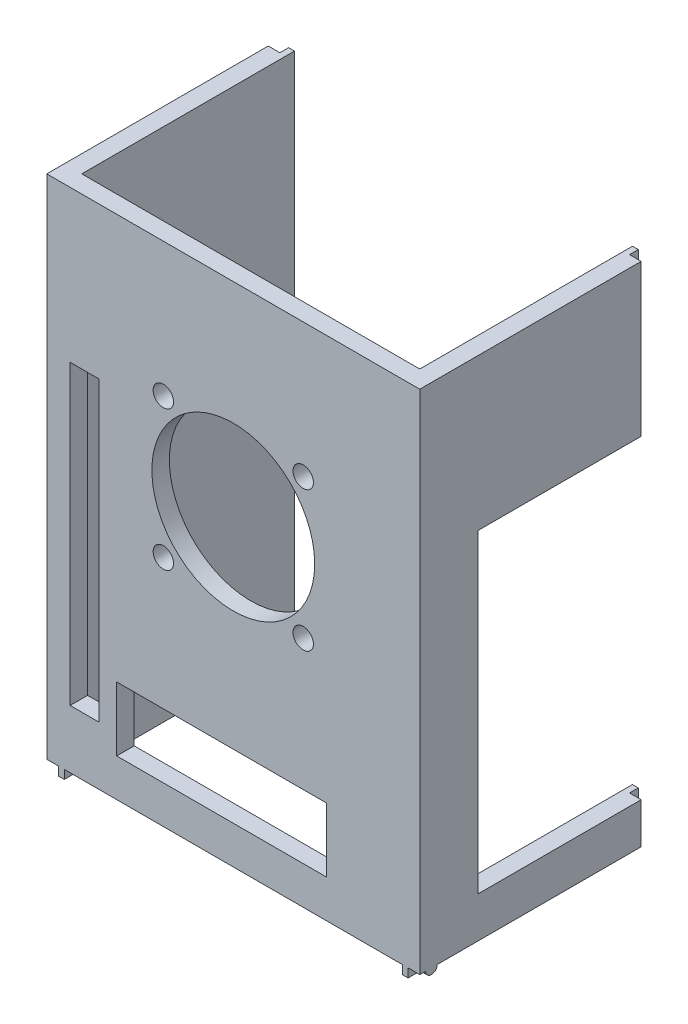
SolidWorks part; units mm, degrees
ref_plane "前视基准面" through (0, 0, 0) normal (0, 0, 1) x (1, 0, 0)
ref_plane "上视基准面" through (0, 0, 0) normal (0, 1, 0) x (1, 0, 0)
ref_plane "右视基准面" through (0, 0, 0) normal (1, 0, 0) x (0, 0, -1)
sketch "草图2" plane through (0, 0, 0) normal (0, 1, 0) x (1, 0, 0)
  line L0 (-3.2692, 5.7115) -> (-3.2692, 2.7115)
  line L1 (-3.2692, 2.7115) -> (-4.7692, 2.7115)
  line L2 (-4.7692, 2.7115) -> (-4.7692, -19.2885)
  line L3 (-4.7692, -19.2885) -> (57.2308, -19.2885)
  line L4 (57.2308, -19.2885) -> (57.2308, 2.7115)
  line L5 (57.2308, 2.7115) -> (55.7308, 2.7115)
  line L6 (55.7308, 2.7115) -> (55.7308, 5.7115)
  line L7 (55.7308, 5.7115) -> (54.2308, 5.7115)
  line L8 (54.2308, 5.7115) -> (54.2308, -16.2885)
  line L9 (54.2308, -16.2885) -> (-1.7692, -16.2885)
  line L10 (-1.7692, -16.2885) -> (-1.7692, 5.7115)
  line L11 (-1.7692, 5.7115) -> (-3.2692, 5.7115)
  dimension "D1" = 1.5
  dimension "D2" = 1.5
  dimension "D3" = 22
  dimension "D4" = 3
  dimension "D5" = 1.5
  dimension "D6" = 1.5
  dimension "D7" = 3
  dimension "D8" = 3
  dimension "D9" = 62
extrude "凸台-拉伸1" add sketch "草图2" along normal blind 88
sketch "草图3" plane through (0, 0, 0) normal (0, -1, 0) x (1, 0, 0)
  line L0 (26.2308, 19.2885) -> (26.2308, 3.3282) construction
  line L1 (-3.2692, -5.7115) -> (-1.7692, -5.7115)
  line L2 (-3.2692, -5.7115) -> (-3.2692, 16.2885)
  line L3 (-3.2692, 16.2885) -> (-1.7692, 16.2885)
  line L4 (-1.7692, -5.7115) -> (-1.7692, 16.2885)
  line L5 (-3.2692, -5.7115) -> (-1.7692, 16.2885) construction
  line L6 (-3.2692, 16.2885) -> (-1.7692, -5.7115) construction
  line L7 (-4.7692, 19.2885) -> (57.2308, 19.2885) construction
  line L8 (55.7308, 16.2885) -> (54.2308, -5.7115) construction
  line L9 (55.7308, -5.7115) -> (54.2308, 16.2885) construction
  line L10 (54.2308, -5.7115) -> (54.2308, 16.2885)
  line L11 (55.7308, 16.2885) -> (54.2308, 16.2885)
  line L12 (55.7308, -5.7115) -> (55.7308, 16.2885)
  line L13 (55.7308, -5.7115) -> (54.2308, -5.7115)
  point P4 (-2.5192, 5.2885)
  point P15 (54.9808, 5.2885)
extrude "凸台-拉伸2" add sketch "草图3" along normal blind 3
sketch "草图4" plane through (0, 0, -2.7115) normal (0, 0, -1) x (-1, 0, 0)
  line L0 (-55.7308, 88) -> (-55.7308, 0) construction
  line L1 (-55.7308, 16.69) -> (-54.2308, 16.69)
  line L2 (-55.7308, 16.69) -> (-55.7308, 44.69)
  line L3 (-55.7308, 44.69) -> (-54.2308, 44.69)
  line L4 (-54.2308, 16.69) -> (-54.2308, 44.69)
  line L5 (-55.7308, 16.69) -> (-54.2308, 44.69) construction
  line L6 (-55.7308, 44.69) -> (-54.2308, 16.69) construction
  line L7 (-57.2308, 0) -> (-55.7308, 0) construction
  point P4 (-54.9808, 30.69)
  dimension "D1" = 16.69
  dimension "D2" = 28
  dimension "D3" = 1.5
extrude "切除-拉伸1" cut sketch "草图4" along normal blind 13
sketch "草图5" plane through (0, 0, -2.7115) normal (0, 0, -1) x (-1, 0, 0)
  line L0 (-57.2308, 88) -> (-57.2308, 0) construction
  line L1 (-57.2308, 9) -> (-54.2308, 9)
  line L2 (-57.2308, 9) -> (-57.2308, 61)
  line L3 (-57.2308, 61) -> (-54.2308, 61)
  line L4 (-54.2308, 9) -> (-54.2308, 61)
  line L5 (-57.2308, 9) -> (-54.2308, 61) construction
  line L6 (-57.2308, 61) -> (-54.2308, 9) construction
  line L7 (-57.2308, 0) -> (-55.7308, 0) construction
  point P4 (-55.7308, 35)
  dimension "D1" = 3
  dimension "D2" = 9
  dimension "D3" = 52
extrude "切除-拉伸2" cut sketch "草图5" against normal mid plane 12
sketch "草图6" plane through (-4.7692, 0, 0) normal (-1, 0, 0) x (0, 0, 1)
  line L1 (-2.7115, 0) -> (19.2885, 0) construction
  circle A0 centre (17.2885, 0) radius 1
  dimension "D1" = 2
sketch "草图7" plane through (0, 0, 16.2885) normal (0, 0, 1) x (1, 0, 0)
  line L4 (55.7308, 0) -> (54.2308, 0)
  line L5 (54.2308, 0) -> (54.2308, -3)
  line L6 (54.2308, -3) -> (55.7308, -3)
  line L7 (55.7308, -3) -> (55.7308, 0)
  line L8 (55.7308, 0) -> (54.2308, 0)
  line L9 (54.2308, 0) -> (54.2308, -3)
  line L10 (54.2308, -3) -> (55.7308, -3)
  line L11 (55.7308, -3) -> (55.7308, 0)
  line L12 (-1.7692, 0) -> (-3.2692, 0)
  line L13 (-3.2692, 0) -> (-3.2692, -3)
  line L14 (-3.2692, -3) -> (-1.7692, -3)
  line L15 (-1.7692, -3) -> (-1.7692, 0)
  line L16 (-1.7692, 0) -> (-3.2692, 0)
  line L17 (-3.2692, 0) -> (-3.2692, -3)
  line L18 (-3.2692, -3) -> (-1.7692, -3)
  line L19 (-1.7692, -3) -> (-1.7692, 0)
  dimension "D1" = 0
  dimension "D2" = 0
extrude "凸台-拉伸4" add sketch "草图7" along normal up to surface (3 mm away) up to face at (26.2308, 44, 19.2885)
extrude "凸台-拉伸7" add sketch "草图6" against normal through all
sketch "草图8" plane through (57.2308, 0, 0) normal (1, 0, 0) x (0, 0, -1)
  line L9 (-19.2885, 0) -> (-18.2885, 0)
  line L10 (-16.2885, 0) -> (2.7115, 0)
  line L11 (2.7115, 0) -> (2.7115, 9)
  line L12 (2.7115, 9) -> (-3.2885, 9)
  line L13 (-3.2885, 9) -> (-3.2885, 61)
  line L14 (-3.2885, 61) -> (2.7115, 61)
  line L15 (2.7115, 61) -> (2.7115, 88)
  line L16 (2.7115, 88) -> (-19.2885, 88)
  line L17 (-19.2885, 88) -> (-19.2885, 0)
  line L18 (-19.2885, 0) -> (-18.2885, 0)
  line L19 (-16.2885, 0) -> (2.7115, 0)
  line L20 (2.7115, 0) -> (2.7115, 9)
  line L21 (2.7115, 9) -> (-3.2885, 9)
  line L22 (-3.2885, 9) -> (-3.2885, 61)
  line L23 (-3.2885, 61) -> (2.7115, 61)
  line L24 (2.7115, 61) -> (2.7115, 88)
  line L25 (2.7115, 88) -> (-19.2885, 88)
  line L26 (-19.2885, 88) -> (-19.2885, 0)
  arc A1 (-18.2885, 0) -> (-16.2885, 0) centre (-17.2885, 0) ccw
  arc A2 (-18.2885, 0) -> (-16.2885, 0) centre (-17.2885, 0) ccw
  dimension "D1" = 0
extrude "凸台-拉伸8" add sketch "草图8" along normal blind 1
sketch "草图9" plane through (-4.7692, 0, 0) normal (-1, 0, 0) x (0, 0, 1)
  line L5 (-2.7115, 0) -> (16.2885, 0)
  line L6 (18.2885, 0) -> (19.2885, 0)
  line L7 (19.2885, 0) -> (19.2885, 88)
  line L8 (19.2885, 88) -> (-2.7115, 88)
  line L9 (-2.7115, 88) -> (-2.7115, 0)
  line L10 (-2.7115, 0) -> (16.2885, 0)
  line L11 (18.2885, 0) -> (19.2885, 0)
  line L12 (19.2885, 0) -> (19.2885, 88)
  line L13 (19.2885, 88) -> (-2.7115, 88)
  line L14 (-2.7115, 88) -> (-2.7115, 0)
  arc A1 (16.2885, 0) -> (18.2885, 0) centre (17.2885, 0) ccw
  arc A2 (16.2885, 0) -> (18.2885, 0) centre (17.2885, 0) ccw
  dimension "D1" = 0
extrude "凸台-拉伸9" add sketch "草图9" along normal blind 1
sketch "草图10" plane through (-3.2692, 0, 0) normal (-1, 0, 0) x (0, 0, 1)
  line L7 (19.2885, 0) -> (18.2885, 0)
  line L8 (16.2885, 0) -> (-2.7115, 0)
  line L9 (-2.7115, 0) -> (-2.7115, 88)
  line L10 (-2.7115, 88) -> (-5.7115, 88)
  line L11 (-5.7115, 88) -> (-5.7115, -3)
  line L12 (-5.7115, -3) -> (19.2885, -3)
  line L13 (19.2885, -3) -> (19.2885, 0)
  line L14 (19.2885, 0) -> (18.2885, 0)
  line L15 (16.2885, 0) -> (-2.7115, 0)
  line L16 (-2.7115, 0) -> (-2.7115, 88)
  line L17 (-2.7115, 88) -> (-5.7115, 88)
  line L18 (-5.7115, 88) -> (-5.7115, -3)
  line L19 (-5.7115, -3) -> (19.2885, -3)
  line L20 (19.2885, -3) -> (19.2885, 0)
  arc A1 (16.2885, 0) -> (18.2885, 0) centre (17.2885, 0) ccw
  arc A2 (16.2885, 0) -> (18.2885, 0) centre (17.2885, 0) ccw
  dimension "D1" = 0
extrude "凸台-拉伸10" add sketch "草图10" along normal blind 1
sketch "草图11" plane through (55.7308, 0, 0) normal (1, 0, 0) x (0, 0, -1)
  line L7 (2.7115, 0) -> (-16.2885, 0)
  line L8 (-18.2885, 0) -> (-19.2885, 0)
  line L9 (-19.2885, 0) -> (-19.2885, -3)
  line L10 (-19.2885, -3) -> (5.7115, -3)
  line L11 (5.7115, -3) -> (5.7115, 9)
  line L12 (5.7115, 9) -> (2.7115, 9)
  line L13 (2.7115, 9) -> (2.7115, 0)
  line L14 (2.7115, 0) -> (-16.2885, 0)
  line L15 (-18.2885, 0) -> (-19.2885, 0)
  line L16 (-19.2885, 0) -> (-19.2885, -3)
  line L17 (-19.2885, -3) -> (5.7115, -3)
  line L18 (5.7115, -3) -> (5.7115, 9)
  line L19 (5.7115, 9) -> (2.7115, 9)
  line L20 (2.7115, 9) -> (2.7115, 0)
  arc A1 (-18.2885, 0) -> (-16.2885, 0) centre (-17.2885, 0) ccw
  arc A2 (-18.2885, 0) -> (-16.2885, 0) centre (-17.2885, 0) ccw
  dimension "D1" = 0
extrude "凸台-拉伸11" add sketch "草图11" along normal blind 1
sketch "草图12" plane through (55.7308, 0, 0) normal (1, 0, 0) x (0, 0, -1)
  line L4 (2.7115, 88) -> (2.7115, 61)
  line L5 (2.7115, 61) -> (5.7115, 61)
  line L6 (5.7115, 61) -> (5.7115, 88)
  line L7 (5.7115, 88) -> (2.7115, 88)
  line L8 (2.7115, 88) -> (2.7115, 61)
  line L9 (2.7115, 61) -> (5.7115, 61)
  line L10 (5.7115, 61) -> (5.7115, 88)
  line L11 (5.7115, 88) -> (2.7115, 88)
  dimension "D1" = 0
extrude "凸台-拉伸12" add sketch "草图12" along normal blind 1
sketch "草图13" plane through (-1.7692, 0, 0) normal (1, 0, 0) x (0, 0, -1)
  line L6 (-16.2885, 88) -> (-16.2885, 0)
  line L7 (-18.2885, 0) -> (-19.2885, 0)
  line L8 (-19.2885, 0) -> (-19.2885, -3)
  line L9 (-19.2885, -3) -> (5.7115, -3)
  line L10 (5.7115, -3) -> (5.7115, 88)
  line L11 (5.7115, 88) -> (-16.2885, 88)
  line L12 (-16.2885, 88) -> (-16.2885, 0)
  line L13 (-18.2885, 0) -> (-19.2885, 0)
  line L14 (-19.2885, 0) -> (-19.2885, -3)
  line L15 (-19.2885, -3) -> (5.7115, -3)
  line L16 (5.7115, -3) -> (5.7115, 88)
  line L17 (5.7115, 88) -> (-16.2885, 88)
  arc A1 (-18.2885, 0) -> (-16.2885, 0) centre (-17.2885, 0) ccw
  arc A2 (-18.2885, 0) -> (-16.2885, 0) centre (-17.2885, 0) ccw
  dimension "D1" = 0
extrude "切除-拉伸3" cut sketch "草图13" against normal blind 1
sketch "草图14" plane through (54.2308, 0, 0) normal (-1, 0, 0) x (0, 0, 1)
  line L10 (19.2885, 0) -> (18.2885, 0)
  line L11 (16.2885, 0) -> (16.2885, 88)
  line L12 (16.2885, 88) -> (-5.7115, 88)
  line L13 (-5.7115, 88) -> (-5.7115, 61)
  line L14 (-5.7115, 61) -> (3.2885, 61)
  line L15 (3.2885, 61) -> (3.2885, 9)
  line L16 (3.2885, 9) -> (-5.7115, 9)
  line L17 (-5.7115, 9) -> (-5.7115, -3)
  line L18 (-5.7115, -3) -> (19.2885, -3)
  line L19 (19.2885, -3) -> (19.2885, 0)
  line L20 (19.2885, 0) -> (18.2885, 0)
  line L21 (16.2885, 0) -> (16.2885, 88)
  line L22 (16.2885, 88) -> (-5.7115, 88)
  line L23 (-5.7115, 88) -> (-5.7115, 61)
  line L24 (-5.7115, 61) -> (3.2885, 61)
  line L25 (3.2885, 61) -> (3.2885, 9)
  line L26 (3.2885, 9) -> (-5.7115, 9)
  line L27 (-5.7115, 9) -> (-5.7115, -3)
  line L28 (-5.7115, -3) -> (19.2885, -3)
  line L29 (19.2885, -3) -> (19.2885, 0)
  arc A1 (16.2885, 0) -> (18.2885, 0) centre (17.2885, 0) ccw
  arc A2 (16.2885, 0) -> (18.2885, 0) centre (17.2885, 0) ccw
  dimension "D1" = 0
extrude "切除-拉伸4" cut sketch "草图14" against normal blind 1
sketch "草图15" plane through (0, -3, 0) normal (0, -1, 0) x (1, 0, 0)
  line L4 (-2.7692, -5.7115) -> (-2.7692, 19.2885)
  line L5 (-2.7692, 19.2885) -> (-4.2692, 19.2885)
  line L6 (-4.2692, 19.2885) -> (-4.2692, -5.7115)
  line L7 (-4.2692, -5.7115) -> (-2.7692, -5.7115)
  line L8 (-2.7692, -5.7115) -> (-2.7692, 19.2885)
  line L9 (-2.7692, 19.2885) -> (-4.2692, 19.2885)
  line L10 (-4.2692, 19.2885) -> (-4.2692, -5.7115)
  line L11 (-4.2692, -5.7115) -> (-2.7692, -5.7115)
  dimension "D1" = 0
extrude "切除-拉伸5" cut sketch "草图15" against normal blind 1
sketch "草图16" plane through (0, -3, 0) normal (0, -1, 0) x (1, 0, 0)
  line L4 (56.7308, 19.2885) -> (55.2308, 19.2885)
  line L5 (55.2308, 19.2885) -> (55.2308, -5.7115)
  line L6 (55.2308, -5.7115) -> (56.7308, -5.7115)
  line L7 (56.7308, -5.7115) -> (56.7308, 19.2885)
  line L8 (56.7308, 19.2885) -> (55.2308, 19.2885)
  line L9 (55.2308, 19.2885) -> (55.2308, -5.7115)
  line L10 (55.2308, -5.7115) -> (56.7308, -5.7115)
  line L11 (56.7308, -5.7115) -> (56.7308, 19.2885)
  dimension "D1" = 0
extrude "切除-拉伸6" cut sketch "草图16" against normal blind 1
sketch "草图17" plane through (0, 0, -5.7115) normal (0, 0, -1) x (-1, 0, 0)
  line L4 (2.7692, -2) -> (4.2692, -2)
  line L5 (4.2692, -2) -> (4.2692, 88)
  line L6 (4.2692, 88) -> (2.7692, 88)
  line L7 (2.7692, 88) -> (2.7692, -2)
  line L8 (2.7692, -2) -> (4.2692, -2)
  line L9 (4.2692, -2) -> (4.2692, 88)
  line L10 (4.2692, 88) -> (2.7692, 88)
  line L11 (2.7692, 88) -> (2.7692, -2)
  dimension "D1" = 0
extrude "切除-拉伸7" cut sketch "草图17" against normal blind 1
sketch "草图18" plane through (0, 0, -5.7115) normal (0, 0, -1) x (-1, 0, 0)
  line L4 (-56.7308, -2) -> (-55.2308, -2)
  line L5 (-55.2308, -2) -> (-55.2308, 9)
  line L6 (-55.2308, 9) -> (-56.7308, 9)
  line L7 (-56.7308, 9) -> (-56.7308, -2)
  line L8 (-56.7308, -2) -> (-55.2308, -2)
  line L9 (-55.2308, -2) -> (-55.2308, 9)
  line L10 (-55.2308, 9) -> (-56.7308, 9)
  line L11 (-56.7308, 9) -> (-56.7308, -2)
  dimension "D1" = 0
extrude "切除-拉伸8" cut sketch "草图18" against normal blind 1
sketch "草图19" plane through (0, 0, -5.7115) normal (0, 0, -1) x (-1, 0, 0)
  line L4 (-55.2308, 61) -> (-55.2308, 88)
  line L5 (-55.2308, 88) -> (-56.7308, 88)
  line L6 (-56.7308, 88) -> (-56.7308, 61)
  line L7 (-56.7308, 61) -> (-55.2308, 61)
  line L8 (-55.2308, 61) -> (-55.2308, 88)
  line L9 (-55.2308, 88) -> (-56.7308, 88)
  line L10 (-56.7308, 88) -> (-56.7308, 61)
  line L11 (-56.7308, 61) -> (-55.2308, 61)
  dimension "D1" = 0
extrude "切除-拉伸9" cut sketch "草图19" against normal blind 1
sketch "草图20" plane through (0, 0, 19.2885) normal (0, 0, 1) x (1, 0, 0)
  line L12 (55.2308, -2) -> (56.7308, -2)
  line L13 (56.7308, -2) -> (56.7308, 0)
  line L14 (56.7308, 0) -> (58.2308, 0)
  line L15 (58.2308, 0) -> (58.2308, 88)
  line L16 (58.2308, 88) -> (-5.7692, 88)
  line L17 (-5.7692, 88) -> (-5.7692, 0)
  line L18 (-5.7692, 0) -> (-4.2692, 0)
  line L19 (-4.2692, 0) -> (-4.2692, -2)
  line L20 (-4.2692, -2) -> (-2.7692, -2)
  line L21 (-2.7692, -2) -> (-2.7692, 0)
  line L22 (-2.7692, 0) -> (55.2308, 0)
  line L23 (55.2308, 0) -> (55.2308, -2)
  line L24 (55.2308, -2) -> (56.7308, -2)
  line L25 (56.7308, -2) -> (56.7308, 0)
  line L26 (56.7308, 0) -> (58.2308, 0)
  line L27 (58.2308, 0) -> (58.2308, 88)
  line L28 (58.2308, 88) -> (-5.7692, 88)
  line L29 (-5.7692, 88) -> (-5.7692, 0)
  line L30 (-5.7692, 0) -> (-4.2692, 0)
  line L31 (-4.2692, 0) -> (-4.2692, -2)
  line L32 (-4.2692, -2) -> (-2.7692, -2)
  line L33 (-2.7692, -2) -> (-2.7692, 0)
  line L34 (-2.7692, 0) -> (55.2308, 0)
  line L35 (55.2308, 0) -> (55.2308, -2)
  dimension "D1" = 0
extrude "凸台-拉伸13" add sketch "草图20" along normal blind 1
sketch "草图21" plane through (0, 0, 16.2885) normal (0, 0, -1) x (-1, 0, 0)
  line L4 (-55.2308, 0) -> (2.7692, 0)
  line L5 (2.7692, 0) -> (2.7692, 88)
  line L6 (2.7692, 88) -> (-55.2308, 88)
  line L7 (-55.2308, 88) -> (-55.2308, 0)
  line L8 (-55.2308, 0) -> (2.7692, 0)
  line L9 (2.7692, 0) -> (2.7692, 88)
  line L10 (2.7692, 88) -> (-55.2308, 88)
  line L11 (-55.2308, 88) -> (-55.2308, 0)
  dimension "D1" = 0
extrude "切除-拉伸10" cut sketch "草图21" against normal blind 1
sketch "草图22" plane through (0, 88, 0) normal (0, 1, 0) x (1, 0, 0)
  line L12 (55.2308, 4.7115) -> (55.2308, -17.2885)
  line L13 (55.2308, -17.2885) -> (-2.7692, -17.2885)
  line L14 (-2.7692, -17.2885) -> (-2.7692, 4.7115)
  line L15 (-2.7692, 4.7115) -> (-4.2692, 4.7115)
  line L16 (-4.2692, 4.7115) -> (-4.2692, 2.7115)
  line L17 (-4.2692, 2.7115) -> (-5.7692, 2.7115)
  line L18 (-5.7692, 2.7115) -> (-5.7692, -20.2885)
  line L19 (-5.7692, -20.2885) -> (58.2308, -20.2885)
  line L20 (58.2308, -20.2885) -> (58.2308, 2.7115)
  line L21 (58.2308, 2.7115) -> (56.7308, 2.7115)
  line L22 (56.7308, 2.7115) -> (56.7308, 4.7115)
  line L23 (56.7308, 4.7115) -> (55.2308, 4.7115)
  line L24 (55.2308, 4.7115) -> (55.2308, -17.2885)
  line L25 (55.2308, -17.2885) -> (-2.7692, -17.2885)
  line L26 (-2.7692, -17.2885) -> (-2.7692, 4.7115)
  line L27 (-2.7692, 4.7115) -> (-4.2692, 4.7115)
  line L28 (-4.2692, 4.7115) -> (-4.2692, 2.7115)
  line L29 (-4.2692, 2.7115) -> (-5.7692, 2.7115)
  line L30 (-5.7692, 2.7115) -> (-5.7692, -20.2885)
  line L31 (-5.7692, -20.2885) -> (58.2308, -20.2885)
  line L32 (58.2308, -20.2885) -> (58.2308, 2.7115)
  line L33 (58.2308, 2.7115) -> (56.7308, 2.7115)
  line L34 (56.7308, 2.7115) -> (56.7308, 4.7115)
  line L35 (56.7308, 4.7115) -> (55.2308, 4.7115)
  dimension "D1" = 0
extrude "切除-拉伸11" cut sketch "草图22" against normal blind 1
sketch "草图23" plane through (0, -2, 0) normal (0, -1, 0) x (1, 0, 0)
  line L4 (-4.2692, 20.2885) -> (-4.2692, -4.7115)
  line L5 (-4.2692, -4.7115) -> (-2.7692, -4.7115)
  line L6 (-2.7692, -4.7115) -> (-2.7692, 20.2885)
  line L7 (-2.7692, 20.2885) -> (-4.2692, 20.2885)
  line L8 (-4.2692, 20.2885) -> (-4.2692, -4.7115)
  line L9 (-4.2692, -4.7115) -> (-2.7692, -4.7115)
  line L10 (-2.7692, -4.7115) -> (-2.7692, 20.2885)
  line L11 (-2.7692, 20.2885) -> (-4.2692, 20.2885)
  dimension "D1" = 0
extrude "切除-拉伸12" cut sketch "草图23" against normal blind 0.5
sketch "草图24" plane through (0, -2, 0) normal (0, -1, 0) x (1, 0, 0)
  line L4 (55.2308, 20.2885) -> (55.2308, -4.7115)
  line L5 (55.2308, -4.7115) -> (56.7308, -4.7115)
  line L6 (56.7308, -4.7115) -> (56.7308, 20.2885)
  line L7 (56.7308, 20.2885) -> (55.2308, 20.2885)
  line L8 (55.2308, 20.2885) -> (55.2308, -4.7115)
  line L9 (55.2308, -4.7115) -> (56.7308, -4.7115)
  line L10 (56.7308, -4.7115) -> (56.7308, 20.2885)
  line L11 (56.7308, 20.2885) -> (55.2308, 20.2885)
  dimension "D1" = 0
extrude "切除-拉伸13" cut sketch "草图24" against normal blind 0.5
sketch "草图25" plane through (0, 0, -4.7115) normal (0, 0, -1) x (-1, 0, 0)
  line L4 (2.7692, 87) -> (2.7692, -1.5)
  line L5 (2.7692, -1.5) -> (4.2692, -1.5)
  line L6 (4.2692, -1.5) -> (4.2692, 87)
  line L7 (4.2692, 87) -> (2.7692, 87)
  line L8 (2.7692, 87) -> (2.7692, -1.5)
  line L9 (2.7692, -1.5) -> (4.2692, -1.5)
  line L10 (4.2692, -1.5) -> (4.2692, 87)
  line L11 (4.2692, 87) -> (2.7692, 87)
  dimension "D1" = 0
extrude "切除-拉伸14" cut sketch "草图25" against normal blind 0.5
sketch "草图26" plane through (0, 0, -4.7115) normal (0, 0, -1) x (-1, 0, 0)
  line L4 (-55.2308, 61) -> (-55.2308, 87)
  line L5 (-55.2308, 87) -> (-56.7308, 87)
  line L6 (-56.7308, 87) -> (-56.7308, 61)
  line L7 (-56.7308, 61) -> (-55.2308, 61)
  line L8 (-55.2308, 61) -> (-55.2308, 87)
  line L9 (-55.2308, 87) -> (-56.7308, 87)
  line L10 (-56.7308, 87) -> (-56.7308, 61)
  line L11 (-56.7308, 61) -> (-55.2308, 61)
  dimension "D1" = 0
extrude "切除-拉伸15" cut sketch "草图26" against normal blind 0.5
sketch "草图27" plane through (0, 0, -4.7115) normal (0, 0, -1) x (-1, 0, 0)
  line L4 (-56.7308, 9) -> (-56.7308, -1.5)
  line L5 (-56.7308, -1.5) -> (-55.2308, -1.5)
  line L6 (-55.2308, -1.5) -> (-55.2308, 9)
  line L7 (-55.2308, 9) -> (-56.7308, 9)
  line L8 (-56.7308, 9) -> (-56.7308, -1.5)
  line L9 (-56.7308, -1.5) -> (-55.2308, -1.5)
  line L10 (-55.2308, -1.5) -> (-55.2308, 9)
  line L11 (-55.2308, 9) -> (-56.7308, 9)
  dimension "D1" = 0
extrude "切除-拉伸16" cut sketch "草图27" against normal blind 0.5
sketch "草图28" plane through (-4.2692, 0, 0) normal (-1, 0, 0) x (0, 0, 1)
  line L7 (-2.7115, 87) -> (-4.2115, 87)
  line L8 (-4.2115, 87) -> (-4.2115, -1.5)
  line L9 (-4.2115, -1.5) -> (20.2885, -1.5)
  line L10 (20.2885, -1.5) -> (20.2885, 0)
  line L11 (20.2885, 0) -> (18.2885, 0)
  line L12 (16.2885, 0) -> (-2.7115, 0)
  line L13 (-2.7115, 0) -> (-2.7115, 87)
  line L14 (-2.7115, 87) -> (-4.2115, 87)
  line L15 (-4.2115, 87) -> (-4.2115, -1.5)
  line L16 (-4.2115, -1.5) -> (20.2885, -1.5)
  line L17 (20.2885, -1.5) -> (20.2885, 0)
  line L18 (20.2885, 0) -> (18.2885, 0)
  line L19 (16.2885, 0) -> (-2.7115, 0)
  line L20 (-2.7115, 0) -> (-2.7115, 87)
  arc A1 (16.2885, 0) -> (18.2885, 0) centre (17.2885, 0) ccw
  arc A2 (16.2885, 0) -> (18.2885, 0) centre (17.2885, 0) ccw
  dimension "D1" = 0
extrude "切除-拉伸17" cut sketch "草图28" against normal blind 0.5
sketch "草图29" plane through (56.7308, 0, 0) normal (1, 0, 0) x (0, 0, -1)
  line L4 (2.7115, 61) -> (4.2115, 61)
  line L5 (4.2115, 61) -> (4.2115, 87)
  line L6 (4.2115, 87) -> (2.7115, 87)
  line L7 (2.7115, 87) -> (2.7115, 61)
  line L8 (2.7115, 61) -> (4.2115, 61)
  line L9 (4.2115, 61) -> (4.2115, 87)
  line L10 (4.2115, 87) -> (2.7115, 87)
  line L11 (2.7115, 87) -> (2.7115, 61)
  dimension "D1" = 0
extrude "切除-拉伸18" cut sketch "草图29" against normal blind 0.5
sketch "草图30" plane through (56.7308, 0, 0) normal (1, 0, 0) x (0, 0, -1)
  line L7 (-20.2885, -1.5) -> (4.2115, -1.5)
  line L8 (4.2115, -1.5) -> (4.2115, 9)
  line L9 (4.2115, 9) -> (2.7115, 9)
  line L10 (2.7115, 9) -> (2.7115, 0)
  line L11 (2.7115, 0) -> (-16.2885, 0)
  line L12 (-18.2885, 0) -> (-20.2885, 0)
  line L13 (-20.2885, 0) -> (-20.2885, -1.5)
  line L14 (-20.2885, -1.5) -> (4.2115, -1.5)
  line L15 (4.2115, -1.5) -> (4.2115, 9)
  line L16 (4.2115, 9) -> (2.7115, 9)
  line L17 (2.7115, 9) -> (2.7115, 0)
  line L18 (2.7115, 0) -> (-16.2885, 0)
  line L19 (-18.2885, 0) -> (-20.2885, 0)
  line L20 (-20.2885, 0) -> (-20.2885, -1.5)
  arc A1 (-18.2885, 0) -> (-16.2885, 0) centre (-17.2885, 0) ccw
  arc A2 (-18.2885, 0) -> (-16.2885, 0) centre (-17.2885, 0) ccw
  dimension "D1" = 0
extrude "切除-拉伸19" cut sketch "草图30" against normal blind 0.5
sketch "草图31" plane through (0, 0, 20.2885) normal (0, 0, 1) x (1, 0, 0)
  line L12 (56.2308, -1.5) -> (56.2308, 0)
  line L13 (56.2308, 0) -> (58.2308, 0)
  line L14 (58.2308, 0) -> (58.2308, 87)
  line L15 (58.2308, 87) -> (-5.7692, 87)
  line L16 (-5.7692, 87) -> (-5.7692, 0)
  line L17 (-5.7692, 0) -> (-3.7692, 0)
  line L18 (-3.7692, 0) -> (-3.7692, -1.5)
  line L19 (-3.7692, -1.5) -> (-2.7692, -1.5)
  line L20 (-2.7692, -1.5) -> (-2.7692, 0)
  line L21 (-2.7692, 0) -> (55.2308, 0)
  line L22 (55.2308, 0) -> (55.2308, -1.5)
  line L23 (55.2308, -1.5) -> (56.2308, -1.5)
  line L24 (56.2308, -1.5) -> (56.2308, 0)
  line L25 (56.2308, 0) -> (58.2308, 0)
  line L26 (58.2308, 0) -> (58.2308, 87)
  line L27 (58.2308, 87) -> (-5.7692, 87)
  line L28 (-5.7692, 87) -> (-5.7692, 0)
  line L29 (-5.7692, 0) -> (-3.7692, 0)
  line L30 (-3.7692, 0) -> (-3.7692, -1.5)
  line L31 (-3.7692, -1.5) -> (-2.7692, -1.5)
  line L32 (-2.7692, -1.5) -> (-2.7692, 0)
  line L33 (-2.7692, 0) -> (55.2308, 0)
  line L34 (55.2308, 0) -> (55.2308, -1.5)
  line L35 (55.2308, -1.5) -> (56.2308, -1.5)
  dimension "D1" = 0
extrude "凸台-拉伸14" add sketch "草图31" along normal blind 15
sketch "草图32" plane through (0, 0, 17.2885) normal (0, 0, -1) x (-1, 0, 0)
  line L4 (2.7692, 0) -> (2.7692, 87)
  line L5 (2.7692, 87) -> (-55.2308, 87)
  line L6 (-55.2308, 87) -> (-55.2308, 0)
  line L7 (-55.2308, 0) -> (2.7692, 0)
  line L8 (2.7692, 0) -> (2.7692, 87)
  line L9 (2.7692, 87) -> (-55.2308, 87)
  line L10 (-55.2308, 87) -> (-55.2308, 0)
  line L11 (-55.2308, 0) -> (2.7692, 0)
  dimension "D1" = 0
extrude "切除-拉伸20" cut sketch "草图32" against normal blind 15
sketch "草图33" plane through (-5.7692, 0, 0) normal (-1, 0, 0) x (0, 0, 1)
  circle A0 centre (17.2885, 0) radius 1
extrude "切除-拉伸21" cut sketch "草图33" against normal through all
sketch "草图34" plane through (0, 9, 0) normal (0, 1, 0) x (1, 0, 0)
  line L6 (58.2308, 2.7115) -> (56.2308, 2.7115)
  line L7 (56.2308, 2.7115) -> (56.2308, 4.2115)
  line L8 (56.2308, 4.2115) -> (55.2308, 4.2115)
  line L9 (55.2308, 4.2115) -> (55.2308, -3.2885)
  line L10 (55.2308, -3.2885) -> (58.2308, -3.2885)
  line L11 (58.2308, -3.2885) -> (58.2308, 2.7115)
  line L12 (58.2308, 2.7115) -> (56.2308, 2.7115)
  line L13 (56.2308, 2.7115) -> (56.2308, 4.2115)
  line L14 (56.2308, 4.2115) -> (55.2308, 4.2115)
  line L15 (55.2308, 4.2115) -> (55.2308, -3.2885)
  line L16 (55.2308, -3.2885) -> (58.2308, -3.2885)
  line L17 (58.2308, -3.2885) -> (58.2308, 2.7115)
  dimension "D1" = 0
extrude "切除-拉伸22" cut sketch "草图34" against normal blind 2
sketch "草图35" plane through (0, 0, -2.7115) normal (0, 0, -1) x (-1, 0, 0)
  line L4 (-56.2308, 7) -> (-58.2308, 7)
  line L5 (-58.2308, 7) -> (-58.2308, 0)
  line L6 (-58.2308, 0) -> (-56.2308, 0)
  line L7 (-56.2308, 0) -> (-56.2308, 7)
  line L8 (-56.2308, 7) -> (-58.2308, 7)
  line L9 (-58.2308, 7) -> (-58.2308, 0)
  line L10 (-58.2308, 0) -> (-56.2308, 0)
  line L11 (-56.2308, 0) -> (-56.2308, 7)
  dimension "D1" = 0
extrude "凸台-拉伸15" add sketch "草图35" against normal blind 26
sketch "草图36" plane through (0, 0, -4.2115) normal (0, 0, -1) x (-1, 0, 0)
  line L4 (-55.2308, -1.5) -> (-55.2308, 7)
  line L5 (-55.2308, 7) -> (-56.2308, 7)
  line L6 (-56.2308, 7) -> (-56.2308, -1.5)
  line L7 (-56.2308, -1.5) -> (-55.2308, -1.5)
  line L8 (-55.2308, -1.5) -> (-55.2308, 7)
  line L9 (-55.2308, 7) -> (-56.2308, 7)
  line L10 (-56.2308, 7) -> (-56.2308, -1.5)
  line L11 (-56.2308, -1.5) -> (-55.2308, -1.5)
  dimension "D1" = 0
extrude "凸台-拉伸16" add sketch "草图36" against normal blind 26
sketch "草图37" plane through (0, 0, -2.7115) normal (0, 0, -1) x (-1, 0, 0)
  line L4 (5.7692, 87) -> (3.7692, 87)
  line L5 (3.7692, 87) -> (3.7692, 0)
  line L6 (3.7692, 0) -> (5.7692, 0)
  line L7 (5.7692, 0) -> (5.7692, 87)
  line L8 (5.7692, 87) -> (3.7692, 87)
  line L9 (3.7692, 87) -> (3.7692, 0)
  line L10 (3.7692, 0) -> (5.7692, 0)
  line L11 (5.7692, 0) -> (5.7692, 87)
  dimension "D1" = 0
extrude "凸台-拉伸17" add sketch "草图37" against normal blind 26
sketch "草图38" plane through (0, 0, -4.2115) normal (0, 0, -1) x (-1, 0, 0)
  line L4 (2.7692, -1.5) -> (3.7692, -1.5)
  line L5 (3.7692, -1.5) -> (3.7692, 87)
  line L6 (3.7692, 87) -> (2.7692, 87)
  line L7 (2.7692, 87) -> (2.7692, -1.5)
  line L8 (2.7692, -1.5) -> (3.7692, -1.5)
  line L9 (3.7692, -1.5) -> (3.7692, 87)
  line L10 (3.7692, 87) -> (2.7692, 87)
  line L11 (2.7692, 87) -> (2.7692, -1.5)
  dimension "D1" = 0
extrude "凸台-拉伸18" add sketch "草图38" against normal blind 28
sketch "草图40" plane through (0, 0, 35.2885) normal (0, 0, 1) x (1, 0, 0)
  line L0 (58.2308, 87) -> (-5.7692, 87) construction
  line L2 (26.2308, 87) -> (26.2308, 0) construction
  line L3 (-2.7692, 0) -> (55.2308, 0) construction
  line L4 (38.2308, 87) -> (38.2308, 0) construction
  line L5 (14.2308, 87) -> (14.2308, 0) construction
  line L6 (14.2308, 52) -> (38.2308, 52) construction
  line L7 (14.2308, 64) -> (38.2308, 64) construction
  line L8 (38.2308, 64) -> (38.2308, 40) construction
  line L9 (38.2308, 40) -> (14.2308, 40) construction
  circle A0 centre (38.2308, 64) radius 1.75
  circle A1 centre (38.2308, 40) radius 1.75
  circle A2 centre (14.2308, 40) radius 1.75
  circle A3 centre (14.2308, 64) radius 1.75
  circle A4 centre (26.2308, 52) radius 13.9677
  circle A5 centre (6.2368, 52) radius 4
  circle A6 centre (6.2368, 76) radius 4
  circle A7 centre (6.2368, 28) radius 4
  circle A8 centre (46.2248, 28) radius 4
  circle A9 centre (46.2248, 52) radius 4
  circle A10 centre (46.2248, 76) radius 4
  dimension "D3" = 3.5
  dimension "D5" = 8
  dimension "D1" = 12
  dimension "D2" = 35
  dimension "D4" = 12
extrude "切除-拉伸23" cut sketch "草图40" against normal blind 28
sketch "草图41" plane through (0, 0, 3.2885) normal (0, 0, -1) x (-1, 0, 0)
  line L4 (-55.2308, 7) -> (-55.2308, 61)
  line L5 (-55.2308, 61) -> (-58.2308, 61)
  line L6 (-58.2308, 61) -> (-58.2308, 7)
  line L7 (-58.2308, 7) -> (-55.2308, 7)
  line L8 (-55.2308, 7) -> (-55.2308, 61)
  line L9 (-55.2308, 61) -> (-58.2308, 61)
  line L10 (-58.2308, 61) -> (-58.2308, 7)
  line L11 (-58.2308, 7) -> (-55.2308, 7)
  dimension "D1" = 0
extrude "切除-拉伸25" cut sketch "草图41" against normal blind 22
sketch "草图42" plane through (0, 0, 35.2885) normal (0, 0, 1) x (1, 0, 0)
  line L0 (-5.7692, 9) -> (58.2308, 9) construction
  line L1 (-5.7692, 87) -> (-5.7692, 0) construction
  line L2 (58.2308, 0) -> (58.2308, 87) construction
  line L3 (-2.7692, 0) -> (55.2308, 0) construction
  dimension "D1" = 9
sketch "草图43" plane through (0, 87, 0) normal (0, 1, 0) x (1, 0, 0)
  line L0 (-2.7692, -32.2885) -> (55.2308, -32.2885) construction
  line L1 (11.493, -32.2885) -> (0, -32.2885)
  line L2 (11.493, -32.2885) -> (11.493, -35.2885)
  line L3 (11.493, -35.2885) -> (0, -35.2885)
  line L4 (0, -32.2885) -> (0, -35.2885)
  line L5 (11.493, -32.2885) -> (0, -35.2885) construction
  line L6 (11.493, -35.2885) -> (0, -32.2885) construction
  line L7 (58.2308, -35.2885) -> (-5.7692, -35.2885) construction
  line L8 (26.3519, -36.1207) -> (26.3519, -59.1445) construction
  line L9 (41.2107, -35.2885) -> (52.7037, -32.2885) construction
  line L10 (41.2107, -32.2885) -> (52.7037, -35.2885) construction
  line L11 (52.7037, -32.2885) -> (52.7037, -35.2885)
  line L12 (41.2107, -35.2885) -> (52.7037, -35.2885)
  line L13 (41.2107, -32.2885) -> (41.2107, -35.2885)
  line L14 (41.2107, -32.2885) -> (52.7037, -32.2885)
  point P4 (5.7465, -33.7885)
  point P15 (46.9572, -33.7885)
extrude "凸台-拉伸19" add sketch "草图43" against normal blind 73
sketch "草图44" plane through (0, 0, 35.2885) normal (0, 0, 1) x (1, 0, 0)
  line L0 (-2.7692, 0) -> (-2.7692, 87) construction
  line L1 (-2.7692, 0) -> (55.2308, 0) construction
  line L2 (58.2308, 87) -> (-5.7692, 87) construction
  line L3 (-5.7692, 87) -> (-5.7692, 0) construction
  line L4 (4.2308, 87) -> (4.2308, 0) construction
  line L5 (-5.7692, 62) -> (58.2308, 62) construction
  line L6 (58.2308, 0) -> (58.2308, 87) construction
  line L7 (-5.7692, 9) -> (58.2308, 9) construction
  line L8 (-5.7692, 6) -> (58.2308, 6) construction
  line L13 (-2.7692, 62) -> (4.2308, 8.9821) construction
  line L14 (-2.7692, 8.9821) -> (4.2308, 62) construction
  line L15 (-5.7692, 18) -> (58.2308, 18) construction
  line L16 (42.2308, 0) -> (42.2308, 21.7529) construction
  line L17 (5.2308, 0) -> (5.2308, 18.8795) construction
  line L19 (42.2308, 17.5) -> (6.2308, 17.5)
  line L20 (42.2308, 17.5) -> (42.2308, 6.5)
  line L21 (42.2308, 6.5) -> (6.2308, 6.5)
  line L22 (6.2308, 17.5) -> (6.2308, 6.5)
  line L23 (42.2308, 17.5) -> (6.2308, 6.5) construction
  line L24 (42.2308, 6.5) -> (6.2308, 17.5) construction
  line L25 (-1.7692, 61) -> (3.2308, 61)
  line L26 (-1.7692, 61) -> (-1.7692, 10)
  line L27 (-1.7692, 10) -> (3.2308, 10)
  line L28 (3.2308, 61) -> (3.2308, 10)
  line L29 (-1.7692, 61) -> (3.2308, 10) construction
  line L30 (-1.7692, 10) -> (3.2308, 61) construction
  point P20 (0.7308, 35.4911)
  point P33 (24.2308, 12)
  point P34 (0.7308, 61)
  point P39 (0.7308, 35.5)
  dimension "D1" = 3
  dimension "D2" = 7
  dimension "D3" = 53
  dimension "D4" = 6
  dimension "D5" = 1
  dimension "D6" = 12
  dimension "D7" = 37
  dimension "D8" = 1
  dimension "D9" = 1
  dimension "D10" = 1
  dimension "D11" = 1
  dimension "D12" = 2
  dimension "D13" = 1
  dimension "D14" = 1
extrude "切除-拉伸26" cut sketch "草图44" against normal blind 73
sketch "草图45" plane through (58.2308, 0, 0) normal (1, 0, 0) x (0, 0, -1)
  line L0 (-35.2885, 0) -> (2.7115, 0) construction
  line L1 (-35.2885, 0) -> (-35.2885, 87) construction
  circle A0 centre (-33.2885, 0) radius 1
  dimension "D1" = 2
  dimension "D2" = 2
extrude "凸台-拉伸21" add sketch "草图45" against normal through all
